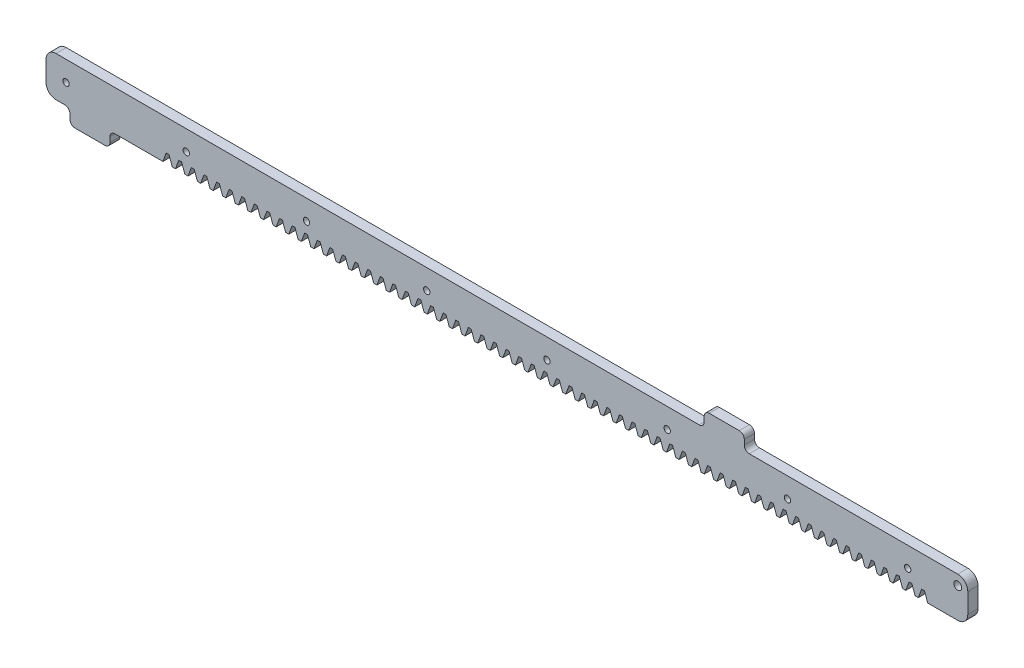
SolidWorks part; units mm, degrees
material "PC High Viscosity"
ref_plane "Front Plane" through (0, 0, 0) normal (0, 0, 1) x (1, 0, 0)
ref_plane "Top Plane" through (0, 0, 0) normal (0, 1, 0) x (1, 0, 0)
ref_plane "Right Plane" through (0, 0, 0) normal (1, 0, 0) x (0, 0, -1)
sketch "Sketch1" plane through (0, 0, 0) normal (0, 0, 1) x (1, 0, 0)
  line L1 (0, 0) -> (15.1308, 0)
  line L2 (0, 0) -> (0, 25.4)
  line L3 (0, 25.4) -> (40.5308, 25.4)
  line L4 (584.2, 0) -> (584.2, 25.4)
  line L7 (533.4, 25.4) -> (584.2, 25.4)
  line L8 (40.5308, 25.4) -> (417.1409, 25.4)
  line L9 (40.5308, 0) -> (584.2, 0)
  line L11 (584.2, 22.7162) -> (577.85, 26.3823) construction
  line L12 (577.85, 26.3823) -> (571.5, 22.7162) construction
  line L13 (571.5, 22.7162) -> (571.5, 15.3838) construction
  line L14 (571.5, 15.3838) -> (577.85, 11.7177) construction
  line L15 (577.85, 11.7177) -> (584.2, 15.3838) construction
  line L16 (584.2, 15.3838) -> (584.2, 22.7162) construction
  line L19 (590.55, 0) -> (590.55, 10.0162) construction
  line L20 (590.55, 10.0162) -> (76.2, 10.0162) construction
  line L21 (76.2, 10.0162) -> (76.2, 0) construction
  line L22 (442.5409, 25.4) -> (533.4, 25.4)
  line L26 (15.1308, 0) -> (15.1308, -9.525)
  line L27 (15.1308, -9.525) -> (40.5308, -9.525)
  line L28 (40.5308, -9.525) -> (40.5308, 0)
  line L29 (417.1409, 25.4) -> (417.1409, 34.925)
  line L30 (417.1409, 34.925) -> (442.5409, 34.925)
  line L31 (442.5409, 34.925) -> (442.5409, 25.4)
  circle A0 centre (577.85, 19.05) radius 2.4892
  circle A1 centre (577.85, 19.05) radius 6.35 construction
  dimension "D5" = 4.9784
  dimension "D6" = 40.5308
  dimension "D7" = 12.7
  dimension "D1" = 584.2
  dimension "D2" = 25.4
  dimension "D3" = 167.0591
  dimension "D4" = 9.525
  dimension "D8" = 25.4
  dimension "D9" = 25.4
extrude "Boss-Extrude1" add sketch "Sketch1" along normal blind 6.477
fillet "Fillet2" radius 6.35 4 edges at (0, 0, 3.2385) (0, 25.4, 3.2385) (584.2, 25.4, 3.2385) (584.2, 0, 3.2385)
sketch "Sketch2" plane through (0, 0, 6.477) normal (0, 0, 1) x (1, 0, 0)
  line L0 (558.8, 0) -> (43.7058, 0)
  line L1 (43.7058, 0) -> (43.7058, 5.715)
  line L2 (43.7058, 5.715) -> (558.8, 5.715)
  line L3 (558.8, 5.715) -> (558.8, 0)
  line L5 (557.8755, 2.54) -> (549.711, 2.54) construction
  line L6 (558.8, 0) -> (556.7199, 5.715)
  line L7 (40.5308, 0) -> (552.8688, 0) construction
  line L8 (552.8688, 0) -> (558.8, 0)
  line L10 (556.7199, 5.715) -> (554.9488, 5.715)
  line L11 (558.8, 0) -> (552.8688, 0)
  line L12 (552.8688, 0) -> (554.9488, 5.715)
  line L13 (554.9488, 5.715) -> (556.7199, 5.715)
  line L14 (558.8, 0) -> (552.8688, 0)
  line L15 (554.9488, 5.715) -> (556.7199, 5.715)
  line L16 (558.8, 0) -> (552.8688, 0)
  line L17 (552.8688, 0) -> (558.8, 0)
  line L19 (556.7199, 5.715) -> (554.9488, 5.715) construction
  line L20 (552.8688, 0) -> (558.8, 0) construction
  line L21 (0, 0) -> (15.1308, 0) construction
  line L22 (584.2, 0) -> (584.2, 25.4) construction
  line L23 (40.5308, 0) -> (584.2, 0) construction
  point P8 (553.7932, 2.54)
  point P16 (557.8755, 2.54)
  dimension "D1" = 70
  dimension "D2" = 2.54
  dimension "D3" = 3.175
  dimension "D4" = 70
  dimension "D5" = 1.7711
  dimension "D6" = 25.4
extrude "Cut-Extrude1" cut sketch "Sketch2" against normal through all contours L12 L0 L8 L6 L2
pattern_linear "LPattern1" count 61 spacing 7.9796 along (-1, 0, 0) of "Cut-Extrude1"
sketch "Sketch3" plane through (0, 0, 6.477) normal (0, 0, 1) x (1, 0, 0)
  line L2 (533.4, 25.4) -> (584.2, 25.4) construction
  line L3 (584.2, 0) -> (584.2, 25.4) construction
  circle A0 centre (546.1, 12.7) radius 2.0193
  dimension "D2" = 4.0386
  dimension "D1" = 12.7
  dimension "D3" = 38.1
extrude "Cut-Extrude2" cut sketch "Sketch3" against normal through all
pattern_linear "LPattern2" count 8 spacing 76.2 along (-1, 0, 0) of "Cut-Extrude2"
fillet "Fillet3" radius 3.175 8 edges at (417.1409, 25.4, 3.2385) (417.1409, 34.925, 3.2385) (442.5409, 34.925, 3.2385) (442.5409, 25.4, 3.2385) (40.5308, -9.525, 3.2385) (40.5308, 0, 3.2385) (15.1308, -9.525, 3.2385) (15.1308, 0, 3.2385)
